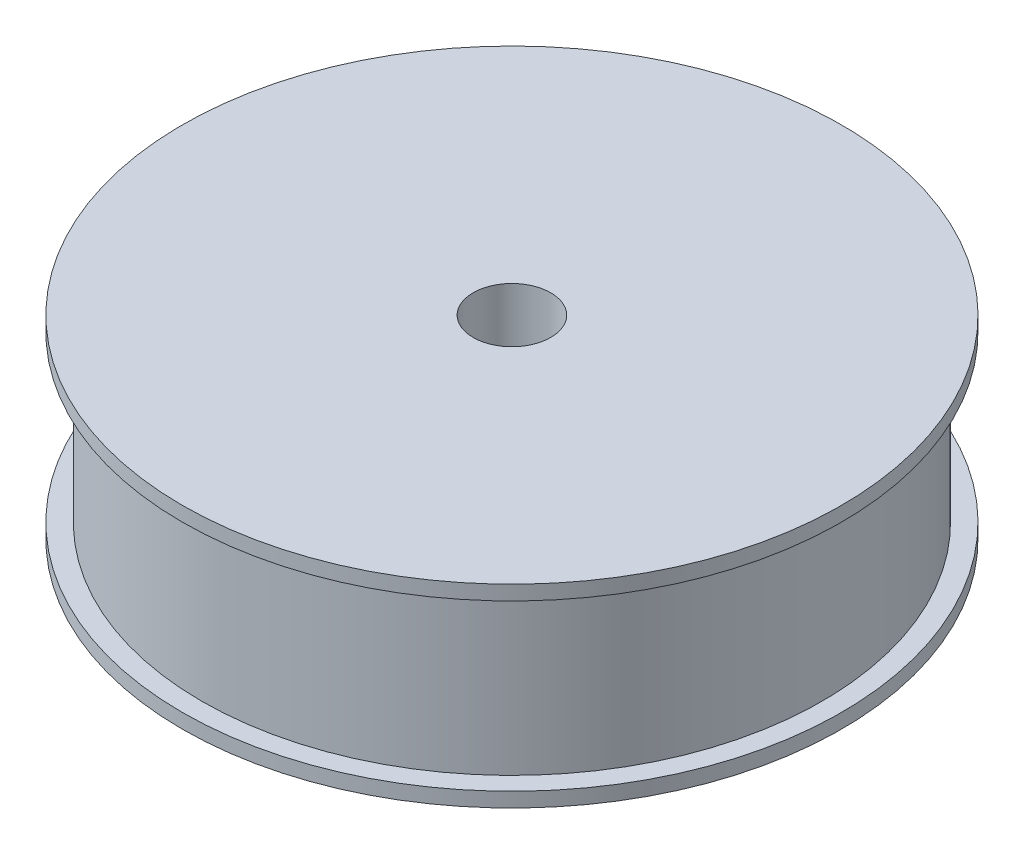
SolidWorks part; units mm, degrees
ref_plane "Front" through (0, 0, 0) normal (0, 0, 1) x (1, 0, 0)
ref_plane "Top" through (0, 0, 0) normal (0, 1, 0) x (1, 0, 0)
ref_plane "Right" through (0, 0, 0) normal (1, 0, 0) x (0, 0, -1)
sketch "Sketch1" plane through (0, 0, 0) normal (1, 0, 0) x (0, 0, -1)
  line L0 (0, 10.3155) -> (0, -12.6924) construction
  line L1 (-13.3377, 0) -> (15.1571, 0) construction
  line L2 (32, -8.5) -> (32, 8.5)
  line L3 (34, 8.5) -> (34, 10)
  line L4 (34, 10) -> (4, 10)
  line L5 (32, 8.5) -> (34, 8.5)
  line L6 (4, 10) -> (4, -10)
  line L7 (32, -8.5) -> (34, -8.5)
  line L8 (34, -8.5) -> (34, -10)
  line L9 (34, -10) -> (4, -10)
  point P11 (32, 0)
  point P15 (4, 0)
  dimension "D1" = 1.5
  dimension "D2" = 10
  dimension "D3" = 34
  dimension "D4" = 2
  dimension "D5" = 4
revolve "Revolve1" add sketch "Sketch1" angle 360 about L0
